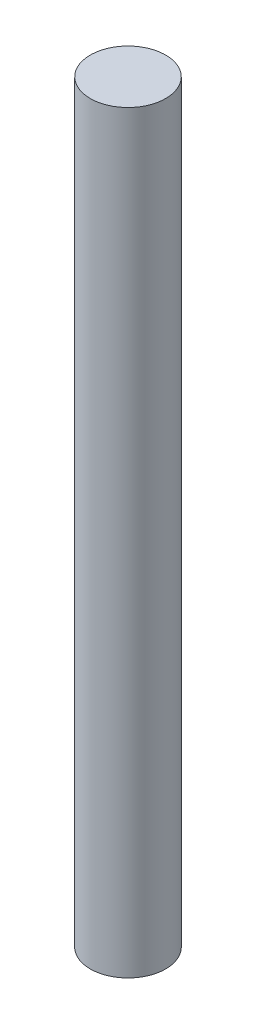
SolidWorks part; units mm, degrees
ref_plane "Front Plane" through (0, 0, 0) normal (0, 0, 1) x (1, 0, 0)
ref_plane "Top Plane" through (0, 0, 0) normal (0, 1, 0) x (1, 0, 0)
ref_plane "Right Plane" through (0, 0, 0) normal (1, 0, 0) x (0, 0, -1)
sketch "Sketch1" plane through (0, 0, 0) normal (0, 1, 0) x (1, 0, 0)
  circle A0 centre (0, 0) radius 4.7625
  dimension "D1" = 9.525
extrude "Boss-Extrude1" add sketch "Sketch1" against normal blind 95.25
